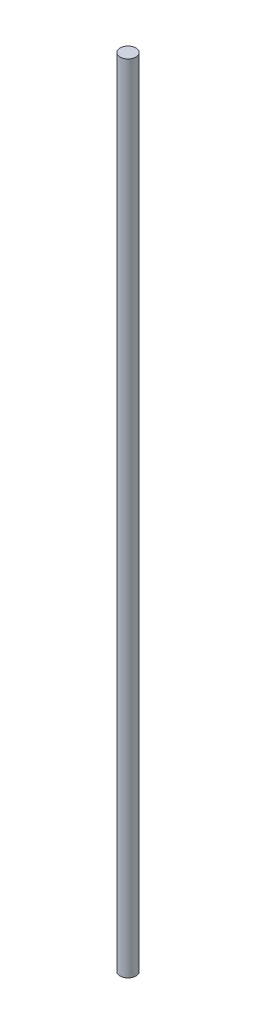
SolidWorks part; units mm, degrees
material "1.4028 (X30Cr13)"
ref_plane "前视基准面" through (0, 0, 0) normal (0, 0, 1) x (1, 0, 0)
ref_plane "上视基准面" through (0, 0, 0) normal (0, 1, 0) x (1, 0, 0)
ref_plane "右视基准面" through (0, 0, 0) normal (1, 0, 0) x (0, 0, -1)
sketch "草图1" plane through (0, 0, 0) normal (0, 1, 0) x (1, 0, 0)
  circle A0 centre (0, 0) radius 1.5
  dimension "D1" = 3
extrude "凸台-拉伸1" add sketch "草图1" along normal blind 150
